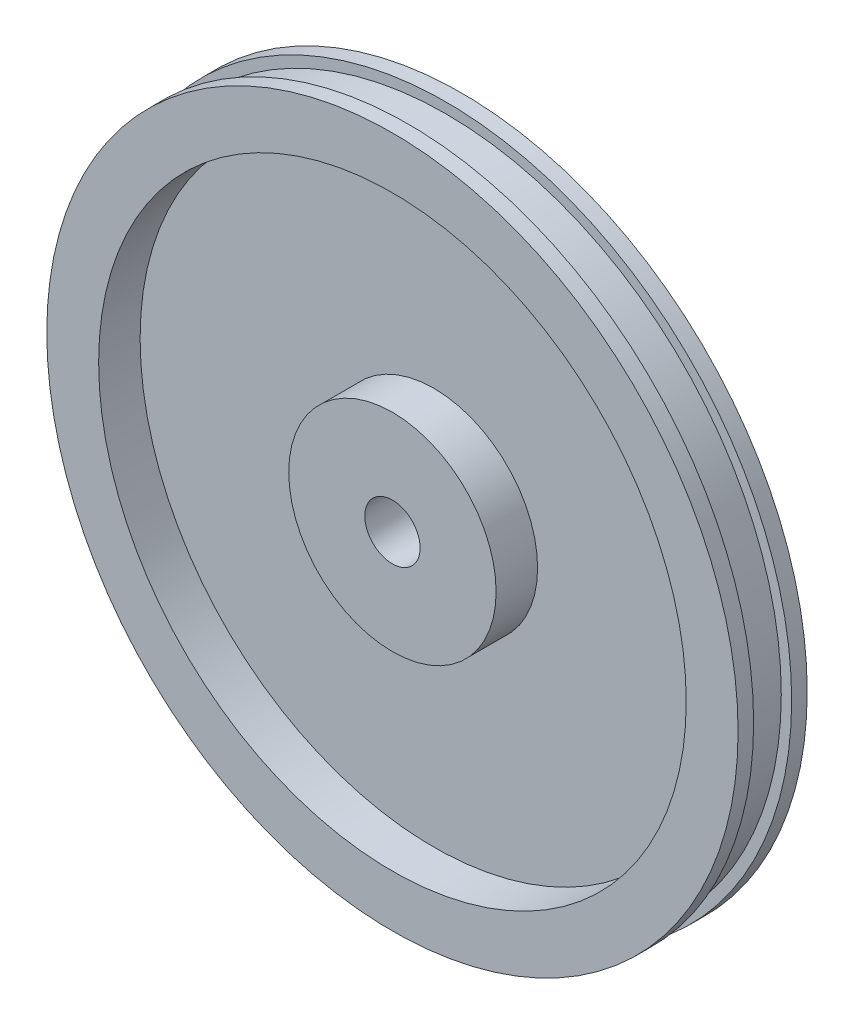
SolidWorks part; units mm, degrees
material "尼龙 101"
ref_plane "前视基准面" through (0, 0, 0) normal (0, 0, 1) x (1, 0, 0)
ref_plane "上视基准面" through (0, 0, 0) normal (0, 1, 0) x (1, 0, 0)
ref_plane "右视基准面" through (0, 0, 0) normal (1, 0, 0) x (0, 0, -1)
sketch "草图1" plane through (0, 0, 0) normal (0, 0, 1) x (1, 0, 0)
  circle A0 centre (0, 0) radius 100
  dimension "D1" = 200
extrude "凸台-拉伸1" add sketch "草图1" along normal blind 20
sketch "草图2" plane through (0, 0, 20) normal (0, 0, 1) x (1, 0, 0)
  circle A0 centre (0, 0) radius 8
  dimension "D1" = 16
extrude "切除-拉伸1" cut sketch "草图2" against normal blind 20
sketch "草图3" plane through (0, 0, 20) normal (0, 0, 1) x (1, 0, 0)
  circle A0 centre (0, 0) radius 30
  circle A1 centre (0, 0) radius 85
  dimension "D1" = 60
  dimension "D2" = 170
extrude "切除-拉伸2" cut sketch "草图3" against normal blind 12
sketch "草图5" plane through (0, 0, 0) normal (0, 1, 0) x (1, 0, 0)
  line L0 (100, -20) -> (100, 0) construction
  line L1 (0, 40.3035) -> (0, -84.1573) construction
  line L3 (97, -4.5) -> (100, -4.5)
  line L4 (97, -4.5) -> (97, -15.5)
  line L5 (97, -15.5) -> (100, -15.5)
  line L6 (100, -4.5) -> (100, -15.5)
  dimension "D2" = 11
  dimension "D3" = 3
revolve "切除-旋转2" cut sketch "草图5" angle 360 about L1
sketch "草图8" plane through (0, 0, 0) normal (0, 0, -1) x (-1, 0, 0)
  circle A0 centre (0, 0) radius 30
  dimension "D1" = 60
extrude "凸台-拉伸2" add sketch "草图8" along normal blind 6
sketch "草图9" plane through (0, 0, -6) normal (0, 0, -1) x (-1, 0, 0)
  circle A0 centre (0, 0) radius 8
  dimension "D1" = 16
extrude "切除-拉伸4" cut sketch "草图9" against normal blind 52
